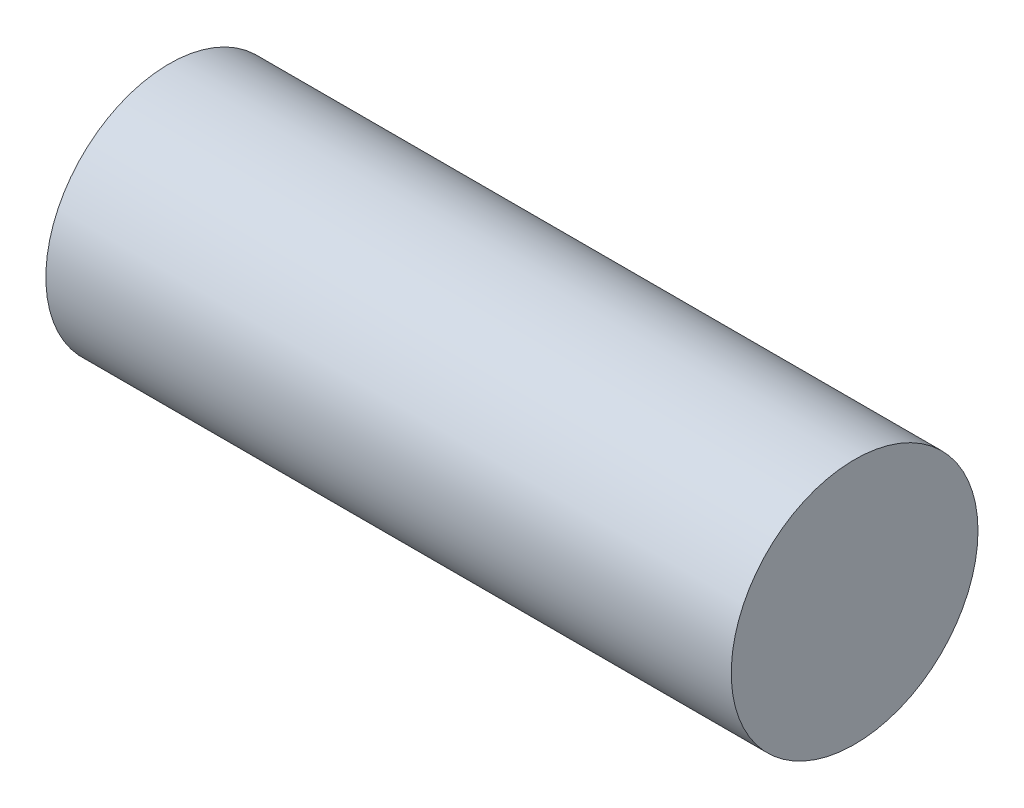
SolidWorks part; units mm, degrees
ref_plane "前视基准面" through (0, 0, 0) normal (0, 0, 1) x (1, 0, 0)
ref_plane "上视基准面" through (0, 0, 0) normal (0, 1, 0) x (1, 0, 0)
ref_plane "右视基准面" through (0, 0, 0) normal (1, 0, 0) x (0, 0, -1)
other "Configuration Table"
sketch "Sketch1" plane through (0, 0, 0) normal (1, 0, 0) x (0, 0, -1)
  circle A0 centre (0, 0) radius 2.25
  dimension "D1" = 4.5
extrude "Boss-Extrude1" add sketch "Sketch1" along normal blind 12.5
